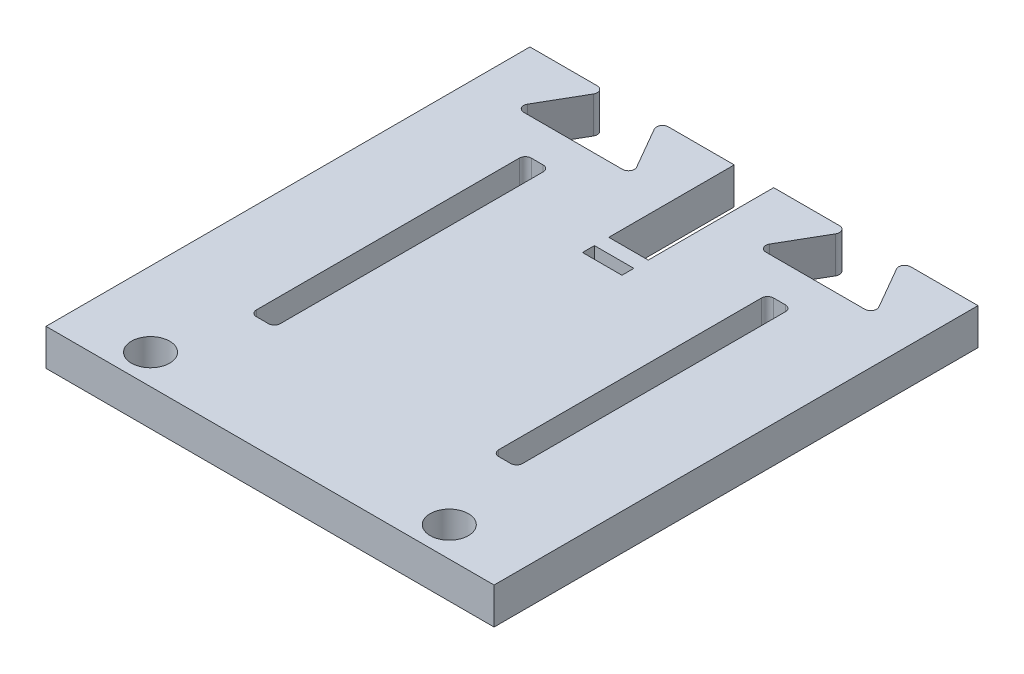
SolidWorks part; units mm, degrees
ref_plane "Front Plane" through (0, 0, 0) normal (0, 0, 1) x (1, 0, 0)
ref_plane "Top Plane" through (0, 0, 0) normal (0, 1, 0) x (1, 0, 0)
ref_plane "Right Plane" through (0, 0, 0) normal (1, 0, 0) x (0, 0, -1)
sketch "Sketch1" plane through (0, 0, 0) normal (0, 1, 0) x (1, 0, 0)
  line L0 (-19.25, 0) -> (-19.25, 40.5)
  line L1 (-19.25, 40.5) -> (-12.25, 40.5)
  line L2 (-12.25, 40.5) -> (-15.1368, 35.5)
  line L3 (-15.1368, 35.5) -> (-5.1368, 35.5)
  line L4 (-5.1368, 35.5) -> (-8.0235, 40.5)
  line L5 (-8.0235, 40.5) -> (8.0235, 40.5)
  line L6 (8.0235, 40.5) -> (5.1368, 35.5)
  line L7 (5.1368, 35.5) -> (15.1368, 35.5)
  line L8 (15.1368, 35.5) -> (12.25, 40.5)
  line L9 (12.25, 40.5) -> (19.25, 40.5)
  line L10 (19.25, 40.5) -> (19.25, 0)
  line L11 (19.25, 0) -> (-19.25, 0)
  point P3 (0, 0)
  dimension "D1" = 40.5
  dimension "D2" = 38.5
  dimension "D3" = 7
  dimension "D4" = 10
  dimension "D5" = 10
  dimension "D6" = 7
  dimension "D7" = 5
  dimension "D11" = 60
  dimension "D12" = 60
  dimension "D13" = 60
extrude "Boss-Extrude1" add sketch "Sketch1" along normal blind 3.05
fillet "Fillet3" radius 0.5 8 edges at (15.1368, 1.525, -35.5) (12.25, 1.525, -40.5) (5.1368, 1.525, -35.5) (8.0235, 1.525, -40.5) (-8.0235, 1.525, -40.5) (-5.1368, 1.525, -35.5) (-15.1368, 1.525, -35.5) (-12.25, 1.525, -40.5)
sketch "Sketch2" plane through (0, 3.05, 0) normal (0, 1, 0) x (1, 0, 0)
  line L0 (0, 0) -> (0, 32.5) construction
  line L3 (1.65, 30) -> (-1.65, 30)
  line L4 (1.65, 30) -> (1.65, 76)
  line L5 (1.65, 76) -> (-1.65, 76)
  line L6 (-1.65, 30) -> (-1.65, 76)
  line L7 (-1.65, 28.8) -> (1.65, 28.8)
  line L8 (-1.65, 28.8) -> (-1.65, 27.8)
  line L9 (-1.65, 27.8) -> (1.65, 27.8)
  line L10 (1.65, 28.8) -> (1.65, 27.8)
  line L11 (-19.25, 0) -> (19.25, 0) construction
  line L12 (-19.25, 0) -> (-19.25, 82.5) construction
  line L13 (-19.25, 82.5) -> (19.25, 82.5) construction
  line L14 (19.25, 0) -> (19.25, 82.5) construction
  point P8 (0, 30)
  point P13 (0, 28.8)
  dimension "D1" = 3.3
  dimension "D2" = 46
  dimension "D3" = 1
  dimension "D4" = 1.2
  dimension "D5" = 82.5
  dimension "D6" = 6.5
extrude "Cut-Extrude1" cut sketch "Sketch2" against normal through all
sketch "Sketch6" plane through (0, 3.05, 0) normal (0, 1, 0) x (1, 0, 0)
  line L0 (0, 0) -> (0, 18.0616) construction
  line L1 (-6.0028, 35.5) -> (-14.2707, 35.5) construction
  line L2 (-11.1368, 32.5) -> (-9.1368, 32.5)
  line L3 (-11.1368, 32.5) -> (-11.1368, 9.5)
  line L4 (-11.1368, 9.5) -> (-9.1368, 9.5)
  line L5 (-9.1368, 32.5) -> (-9.1368, 9.5)
  line L7 (11.1368, 9.5) -> (9.1368, 9.5)
  line L8 (9.1368, 32.5) -> (9.1368, 9.5)
  line L9 (11.1368, 32.5) -> (9.1368, 32.5)
  line L10 (11.1368, 32.5) -> (11.1368, 9.5)
  line L11 (-19.25, 0) -> (19.25, 0) construction
  point P9 (-10.1368, 35.5)
  point P10 (-10.1368, 32.5)
  dimension "D1" = 2
  dimension "D2" = 3
  dimension "D3" = 9.5
extrude "Cut-Extrude2" cut sketch "Sketch6" against normal through all
fillet "Fillet4" radius 0.5 8 edges at (9.1368, 1.525, -9.5) (11.1368, 1.525, -9.5) (11.1368, 1.525, -32.5) (9.1368, 1.525, -32.5) (-11.1368, 1.525, -9.5) (-9.1368, 1.525, -9.5) (-9.1368, 1.525, -32.5) (-11.1368, 1.525, -32.5)
sketch "Head Mounting Hole Locations" plane through (0, 3.05, 0) normal (0, 1, 0) x (1, 0, 0)
  line L0 (0, 0) -> (0, 16.3288) construction
  line L1 (-19.25, 0) -> (19.25, 0) construction
  circle A0 centre (-12.5, 2.5) radius 1.5
  circle A1 centre (12.5, 2.5) radius 1.5
  dimension "D1" = 3
  dimension "D2" = 12.5
  dimension "D3" = 2.5
hole_wizard "M3 Clearance Head Mounting Holes" positions "Sketch4" profile "Sketch5" hole size "M3" standard "ANSI Metric" end condition through all
sketch "Sketch4" plane through (0, 3.05, 0) normal (0, 1, 0) x (1, 0, 0)
  point P0 (-12.5, 2.5)
  point P3 (12.5, 2.5)
sketch "Sketch5" plane through (-12.5, 3.05, -2.5) normal (1, 0, 0) x (0, 0, 1)
  line L0 (0, 0) -> (0, 3.05)
  line L1 (0, 3.05) -> (1.6, 3.05)
  line L2 (1.6, 3.05) -> (1.6, 0)
  line L5 (1.6, 0) -> (0, 0)
  line L11 (0, -6.35) -> (0, 107.95) construction
  dimension "Thru Hole Dia." = 3.2
  dimension "Thru Hole Depth" = 3.05
sketch "Sketch7" plane through (0, 3.05, 0) normal (0, 1, 0) x (1, 0, 0)
  line L0 (-19.25, 40.5) -> (-18.75, 40.5)
  line L1 (-13.116, 40.5) -> (-19.25, 40.5) construction
  line L2 (-18.75, 40.5) -> (-18.75, 0)
  line L3 (-19.25, 0) -> (19.25, 0) construction
  line L4 (-18.75, 0) -> (-19.25, 0)
  line L5 (-19.25, 0) -> (-19.25, 40.5)
  line L6 (19.25, 40.5) -> (18.75, 40.5)
  line L7 (19.25, 40.5) -> (13.116, 40.5) construction
  line L8 (18.75, 40.5) -> (18.75, 0)
  line L9 (18.75, 0) -> (19.25, 0)
  line L10 (19.25, 0) -> (19.25, 40.5)
  dimension "D1" = 0.5
  dimension "D2" = 0.5
extrude "Cut-Extrude3" cut sketch "Sketch7" against normal through all
